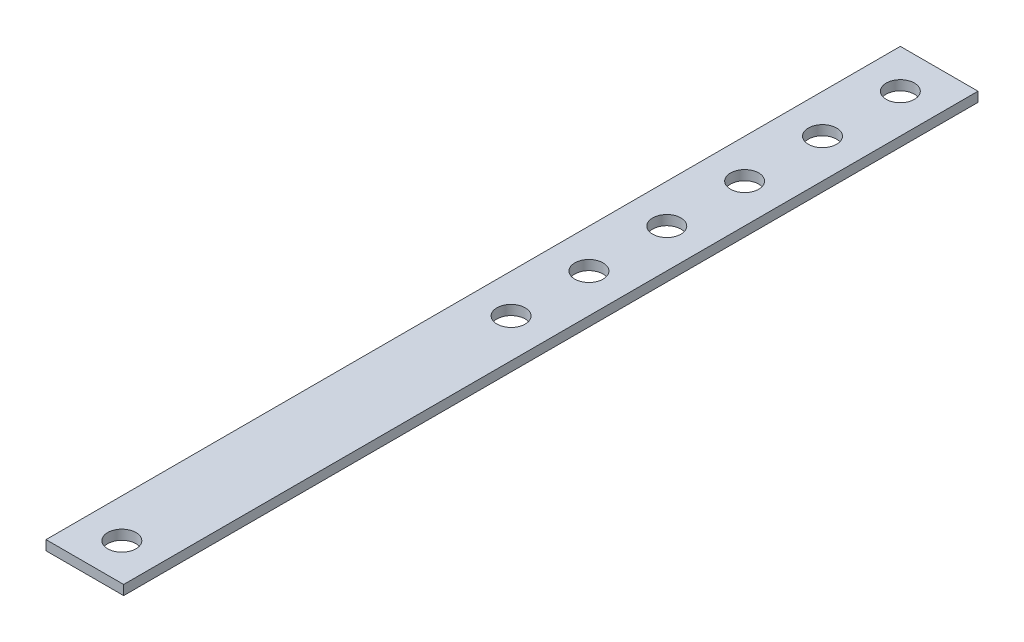
SolidWorks part; units mm, degrees
ref_plane "Front Plane" through (0, 0, 0) normal (0, 0, 1) x (1, 0, 0)
ref_plane "Top Plane" through (0, 0, 0) normal (0, 1, 0) x (1, 0, 0)
ref_plane "Right Plane" through (0, 0, 0) normal (1, 0, 0) x (0, 0, -1)
sketch "Sketch1" plane through (0, 0, 0) normal (0, 1, 0) x (1, 0, 0)
  line L1 (-0.0371, 101.5375) -> (12.6629, 101.5375)
  line L2 (-0.0371, 101.5375) -> (-0.0371, -38.1625)
  line L3 (-0.0371, -38.1625) -> (12.6629, -38.1625)
  line L4 (12.6629, 101.5375) -> (12.6629, -38.1625)
  circle A0 centre (6.3129, 95.1875) radius 2.31
  circle A5 centre (6.3129, 31.5375) radius 2.31
  circle A10 centre (6.3129, -32.1125) radius 2.31
  circle A11 centre (6.3129, 82.4575) radius 2.31 [skipped]
  circle A12 centre (6.3129, 69.7275) radius 2.31 [skipped]
  circle A13 centre (6.3129, 56.9975) radius 2.31 [skipped]
  circle A14 centre (6.3129, 44.2675) radius 2.31 [skipped]
  circle A15 centre (6.3129, 18.8075) radius 2.31 [skipped]
  circle A16 centre (6.3129, 6.0775) radius 2.31 [skipped]
  circle A17 centre (6.3129, -6.6525) radius 2.31 [skipped]
  circle A18 centre (6.3129, -19.3825) radius 2.31 [skipped]
  circle A19 centre (6.3129, 82.4575) radius 2.31
  circle A20 centre (6.3129, 69.7275) radius 2.31
  circle A21 centre (6.3129, 56.9975) radius 2.31
  circle A22 centre (6.3129, 44.2675) radius 2.31
  dimension "D12" = 6.35
  dimension "D1" = 12.7
  dimension "D2" = 139.7
  dimension "D3" = 11
  dimension "D4" = 5
extrude "Boss-Extrude1" add sketch "Sketch1" along normal blind 1.5875
